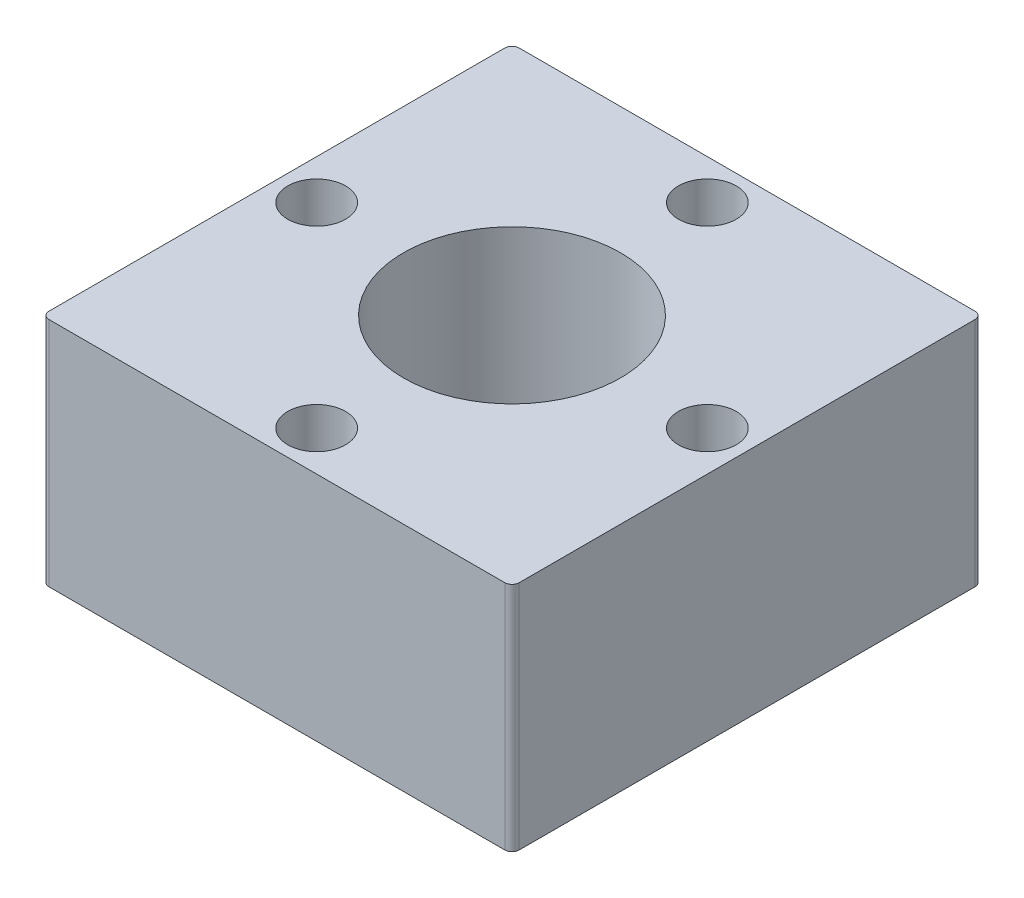
SolidWorks part; units mm, degrees
ref_plane "Alzado" through (0, 0, 0) normal (0, 0, 1) x (1, 0, 0)
ref_plane "Planta" through (0, 0, 0) normal (0, 1, 0) x (1, 0, 0)
ref_plane "Vista lateral" through (0, 0, 0) normal (1, 0, 0) x (0, 0, -1)
sketch "Croquis2" plane through (0, 0, 0) normal (0, 1, 0) x (1, 0, 0)
  line L1 (32.5, 32.5) -> (-32.5, 32.5)
  line L2 (32.5, 32.5) -> (32.5, -32.5)
  line L3 (32.5, -32.5) -> (-32.5, -32.5)
  line L4 (-32.5, 32.5) -> (-32.5, -32.5)
  line L5 (32.5, 32.5) -> (-32.5, -32.5) construction
  line L6 (32.5, -32.5) -> (-32.5, 32.5) construction
  circle A4 centre (0, 0) radius 15
  circle A5 centre (-27, 0) radius 4
  circle A6 centre (27, 0) radius 4
  circle A7 centre (0, 27) radius 4
  circle A8 centre (0, -27) radius 4
  point P0 (0, 0)
  dimension "D3" = 5.5
  dimension "D1" = 65
  dimension "D2" = 65
  dimension "D4" = 5.5
  dimension "D5" = 5.5
  dimension "D6" = 5.5
extrude "Saliente-Extruir1" add sketch "Croquis2" along normal blind 32
sketch "Croquis3" plane through (0, 0, 0) normal (0, 1, 0) x (1, 0, 0)
  circle A0 centre (0, 0) radius 13.5
  circle A1 centre (0, 0) radius 15
extrude "Saliente-Extruir2" add sketch "Croquis3" along normal blind 7
fillet "Redondeo1" radius 1 4 edges at (-32.5, 16, 32.5) (32.5, 16, 32.5) (32.5, 16, -32.5) (-32.5, 16, -32.5)
